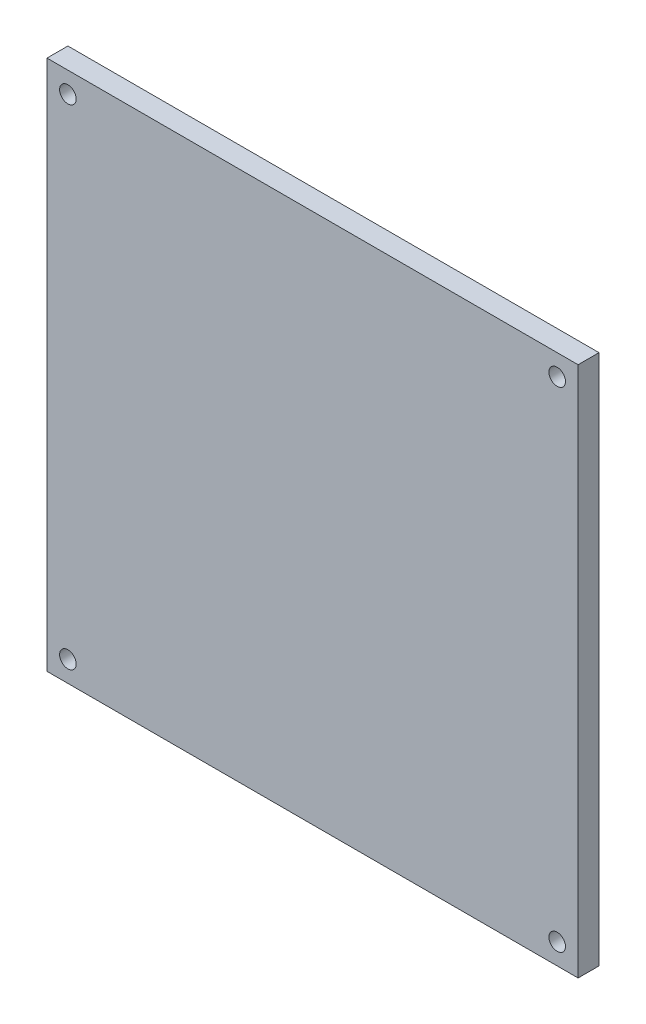
SolidWorks part; units mm, degrees
material "Полибутадиен (PB)"
ref_plane "Спереди" through (0, 0, 0) normal (0, 0, 1) x (1, 0, 0)
ref_plane "Сверху" through (0, 0, 0) normal (0, 1, 0) x (1, 0, 0)
ref_plane "Справа" through (0, 0, 0) normal (1, 0, 0) x (0, 0, -1)
curve "Импортированная кривая1"
curve "Импортированная кривая2"
curve "Импортированная кривая3"
curve "Импортированная кривая4"
curve "Импортированная кривая5"
curve "Импортированная кривая6"
curve "Импортированная кривая7"
curve "Импортированная кривая8"
curve "Импортированная кривая9"
curve "Импортированная кривая10"
curve "Импортированная кривая11"
curve "Импортированная кривая12"
curve "Импортированная кривая13"
curve "Импортированная кривая14"
curve "Импортированная кривая15"
curve "Импортированная кривая16"
curve "Импортированная кривая17"
curve "Импортированная кривая18"
curve "Импортированная кривая19"
curve "Импортированная кривая20"
curve "Импортированная кривая21"
curve "Импортированная кривая22"
curve "Импортированная кривая23"
curve "Импортированная кривая24"
curve "Импортированная кривая25"
curve "Импортированная кривая26"
curve "Импортированная кривая27"
curve "Импортированная кривая28"
curve "Импортированная кривая29"
curve "Импортированная кривая30"
curve "Импортированная кривая31"
curve "Импортированная кривая32"
curve "Импортированная кривая33"
curve "Импортированная кривая34"
curve "Импортированная кривая35"
curve "Импортированная кривая36"
curve "Импортированная кривая37"
curve "Импортированная кривая38"
curve "Импортированная кривая39"
curve "Импортированная кривая40"
curve "Импортированная кривая41"
curve "Импортированная кривая42"
curve "Импортированная кривая43"
curve "Импортированная кривая44"
curve "Импортированная кривая45"
curve "Импортированная кривая46"
curve "Импортированная кривая47"
curve "Импортированная кривая48"
curve "Импортированная кривая49"
curve "Импортированная кривая50"
curve "Импортированная кривая51"
curve "Импортированная кривая52"
curve "Импортированная кривая53"
curve "Импортированная кривая54"
curve "Импортированная кривая55"
curve "Импортированная кривая56"
curve "Импортированная кривая57"
curve "Импортированная кривая58"
curve "Импортированная кривая59"
curve "Импортированная кривая60"
curve "Импортированная кривая61"
curve "Импортированная кривая62"
curve "Импортированная кривая63"
curve "Импортированная кривая64"
curve "Импортированная кривая65"
curve "Импортированная кривая66"
curve "Импортированная кривая67"
curve "Импортированная кривая68"
curve "Импортированная кривая69"
curve "Импортированная кривая70"
curve "Импортированная кривая71"
curve "Импортированная кривая72"
curve "Импортированная кривая73"
curve "Импортированная кривая74"
curve "Импортированная кривая75"
curve "Импортированная кривая76"
curve "Импортированная кривая77"
curve "Импортированная кривая78"
curve "Импортированная кривая79"
curve "Импортированная кривая80"
curve "Импортированная кривая81"
curve "Импортированная кривая82"
curve "Импортированная кривая83"
curve "Импортированная кривая84"
curve "Импортированная кривая85"
curve "Импортированная кривая86"
curve "Импортированная кривая87"
curve "Импортированная кривая88"
curve "Импортированная кривая89"
curve "Импортированная кривая90"
curve "Импортированная кривая91"
curve "Импортированная кривая92"
curve "Импортированная кривая93"
curve "Импортированная кривая94"
curve "Импортированная кривая95"
curve "Импортированная кривая96"
curve "Импортированная кривая97"
curve "Импортированная кривая98"
curve "Импортированная кривая99"
curve "Импортированная кривая100"
curve "Импортированная кривая101"
curve "Импортированная кривая102"
curve "Импортированная кривая103"
curve "Импортированная кривая104"
curve "Импортированная кривая105"
curve "Импортированная кривая106"
curve "Импортированная кривая107"
curve "Импортированная кривая108"
curve "Импортированная кривая109"
curve "Импортированная кривая110"
curve "Импортированная кривая111"
curve "Импортированная кривая112"
curve "Импортированная кривая113"
curve "Импортированная кривая114"
curve "Импортированная кривая115"
curve "Импортированная кривая116"
curve "Импортированная кривая117"
curve "Импортированная кривая118"
curve "Импортированная кривая119"
curve "Импортированная кривая120"
curve "Импортированная кривая121"
curve "Импортированная кривая122"
curve "Импортированная кривая123"
curve "Импортированная кривая124"
curve "Импортированная кривая125"
curve "Импортированная кривая126"
curve "Импортированная кривая127"
curve "Импортированная кривая128"
curve "Импортированная кривая129"
curve "Импортированная кривая130"
curve "Импортированная кривая131"
curve "Импортированная кривая132"
curve "Импортированная кривая133"
curve "Импортированная кривая134"
curve "Импортированная кривая135"
curve "Импортированная кривая136"
curve "Импортированная кривая137"
curve "Импортированная кривая138"
curve "Импортированная кривая139"
curve "Импортированная кривая140"
curve "Импортированная кривая141"
curve "Импортированная кривая142"
curve "Импортированная кривая143"
curve "Импортированная кривая144"
curve "Импортированная кривая145"
curve "Импортированная кривая146"
curve "Импортированная кривая147"
curve "Импортированная кривая148"
curve "Импортированная кривая149"
curve "Импортированная кривая150"
curve "Импортированная кривая151"
curve "Импортированная кривая152"
curve "Импортированная кривая153"
curve "Импортированная кривая154"
curve "Импортированная кривая155"
curve "Импортированная кривая156"
curve "Импортированная кривая157"
curve "Импортированная кривая158"
curve "Импортированная кривая159"
curve "Импортированная кривая160"
curve "Импортированная кривая161"
curve "Импортированная кривая162"
curve "Импортированная кривая163"
curve "Импортированная кривая164"
curve "Импортированная кривая165"
curve "Импортированная кривая166"
curve "Импортированная кривая167"
curve "Импортированная кривая168"
curve "Импортированная кривая169"
curve "Импортированная кривая170"
curve "Импортированная кривая171"
curve "Импортированная кривая172"
curve "Импортированная кривая173"
curve "Импортированная кривая174"
curve "Импортированная кривая175"
curve "Импортированная кривая176"
curve "Импортированная кривая177"
curve "Импортированная кривая178"
curve "Импортированная кривая179"
curve "Импортированная кривая180"
curve "Импортированная кривая181"
curve "Импортированная кривая182"
curve "Импортированная кривая183"
curve "Импортированная кривая184"
curve "Импортированная кривая185"
curve "Импортированная кривая186"
curve "Импортированная кривая187"
curve "Импортированная кривая188"
curve "Импортированная кривая189"
curve "Импортированная кривая190"
curve "Импортированная кривая191"
curve "Импортированная кривая192"
curve "Импортированная кривая193"
curve "Импортированная кривая194"
curve "Импортированная кривая195"
curve "Импортированная кривая196"
curve "Импортированная кривая197"
curve "Импортированная кривая198"
curve "Импортированная кривая199"
curve "Импортированная кривая200"
curve "Импортированная кривая201"
curve "Импортированная кривая202"
curve "Импортированная кривая203"
curve "Импортированная кривая204"
curve "Импортированная кривая205"
curve "Импортированная кривая206"
curve "Импортированная кривая207"
curve "Импортированная кривая208"
curve "Импортированная кривая209"
curve "Импортированная кривая210"
curve "Импортированная кривая211"
curve "Импортированная кривая212"
curve "Импортированная кривая213"
curve "Импортированная кривая214"
curve "Импортированная кривая215"
curve "Импортированная кривая216"
curve "Импортированная кривая217"
curve "Импортированная кривая218"
curve "Импортированная кривая219"
curve "Импортированная кривая220"
curve "Импортированная кривая221"
curve "Импортированная кривая222"
curve "Импортированная кривая223"
curve "Импортированная кривая224"
curve "Импортированная кривая225"
curve "Импортированная кривая226"
curve "Импортированная кривая227"
curve "Импортированная кривая228"
curve "Импортированная кривая229"
curve "Импортированная кривая230"
curve "Импортированная кривая231"
curve "Импортированная кривая232"
curve "Импортированная кривая233"
curve "Импортированная кривая234"
curve "Импортированная кривая235"
curve "Импортированная кривая236"
curve "Импортированная кривая237"
curve "Импортированная кривая238"
curve "Импортированная кривая239"
curve "Импортированная кривая240"
curve "Импортированная кривая241"
curve "Импортированная кривая242"
curve "Импортированная кривая243"
curve "Импортированная кривая244"
curve "Импортированная кривая245"
curve "Импортированная кривая246"
curve "Импортированная кривая247"
curve "Импортированная кривая248"
curve "Импортированная кривая249"
curve "Импортированная кривая250"
curve "Импортированная кривая251"
curve "Импортированная кривая252"
curve "Импортированная кривая253"
curve "Импортированная кривая254"
curve "Импортированная кривая255"
curve "Импортированная кривая256"
curve "Импортированная кривая257"
curve "Импортированная кривая258"
curve "Импортированная кривая259"
curve "Импортированная кривая260"
curve "Импортированная кривая261"
curve "Импортированная кривая262"
curve "Импортированная кривая263"
curve "Импортированная кривая264"
curve "Импортированная кривая265"
curve "Импортированная кривая266"
curve "Импортированная кривая267"
curve "Импортированная кривая268"
curve "Импортированная кривая269"
curve "Импортированная кривая270"
curve "Импортированная кривая271"
curve "Импортированная кривая272"
curve "Импортированная кривая273"
curve "Импортированная кривая274"
curve "Импортированная кривая275"
curve "Импортированная кривая276"
curve "Импортированная кривая277"
curve "Импортированная кривая278"
curve "Импортированная кривая279"
curve "Импортированная кривая280"
curve "Импортированная кривая281"
curve "Импортированная кривая282"
curve "Импортированная кривая283"
curve "Импортированная кривая284"
curve "Импортированная кривая285"
curve "Импортированная кривая286"
curve "Импортированная кривая287"
curve "Импортированная кривая288"
curve "Импортированная кривая289"
curve "Импортированная кривая290"
curve "Импортированная кривая291"
curve "Импортированная кривая292"
curve "Импортированная кривая293"
curve "Импортированная кривая294"
curve "Импортированная кривая295"
curve "Импортированная кривая296"
curve "Импортированная кривая297"
curve "Импортированная кривая298"
curve "Импортированная кривая299"
curve "Импортированная кривая300"
curve "Импортированная кривая301"
curve "Импортированная кривая302"
curve "Импортированная кривая303"
curve "Импортированная кривая304"
curve "Импортированная кривая305"
curve "Импортированная кривая306"
curve "Импортированная кривая307"
curve "Импортированная кривая308"
curve "Импортированная кривая309"
curve "Импортированная кривая310"
curve "Импортированная кривая311"
curve "Импортированная кривая312"
curve "Импортированная кривая313"
curve "Импортированная кривая314"
curve "Импортированная кривая315"
curve "Импортированная кривая316"
curve "Импортированная кривая317"
curve "Импортированная кривая318"
curve "Импортированная кривая319"
curve "Импортированная кривая320"
curve "Импортированная кривая321"
curve "Импортированная кривая322"
curve "Импортированная кривая323"
curve "Импортированная кривая324"
curve "Импортированная кривая325"
curve "Импортированная кривая326"
curve "Импортированная кривая327"
curve "Импортированная кривая328"
curve "Импортированная кривая329"
curve "Импортированная кривая330"
curve "Импортированная кривая331"
curve "Импортированная кривая332"
curve "Импортированная кривая333"
curve "Импортированная кривая334"
curve "Импортированная кривая335"
curve "Импортированная кривая336"
curve "Импортированная кривая337"
curve "Импортированная кривая338"
curve "Импортированная кривая339"
curve "Импортированная кривая340"
curve "Импортированная кривая341"
curve "Импортированная кривая342"
curve "Импортированная кривая343"
curve "Импортированная кривая344"
curve "Импортированная кривая345"
curve "Импортированная кривая346"
curve "Импортированная кривая347"
curve "Импортированная кривая348"
curve "Импортированная кривая349"
curve "Импортированная кривая350"
curve "Импортированная кривая351"
curve "Импортированная кривая352"
curve "Импортированная кривая353"
curve "Импортированная кривая354"
curve "Импортированная кривая355"
curve "Импортированная кривая356"
curve "Импортированная кривая357"
curve "Импортированная кривая358"
curve "Импортированная кривая359"
curve "Импортированная кривая360"
curve "Импортированная кривая361"
curve "Импортированная кривая362"
curve "Импортированная кривая363"
curve "Импортированная кривая364"
curve "Импортированная кривая365"
curve "Импортированная кривая366"
curve "Импортированная кривая367"
curve "Импортированная кривая368"
curve "Импортированная кривая369"
curve "Импортированная кривая370"
curve "Импортированная кривая371"
curve "Импортированная кривая372"
curve "Импортированная кривая373"
curve "Импортированная кривая374"
curve "Импортированная кривая375"
curve "Импортированная кривая376"
curve "Импортированная кривая377"
curve "Импортированная кривая378"
curve "Импортированная кривая379"
curve "Импортированная кривая380"
curve "Импортированная кривая381"
curve "Импортированная кривая382"
curve "Импортированная кривая383"
curve "Импортированная кривая384"
curve "Импортированная кривая385"
curve "Импортированная кривая386"
curve "Импортированная кривая387"
curve "Импортированная кривая388"
curve "Импортированная кривая389"
curve "Импортированная кривая390"
curve "Импортированная кривая391"
curve "Импортированная кривая392"
curve "Импортированная кривая393"
curve "Импортированная кривая394"
curve "Импортированная кривая395"
curve "Импортированная кривая396"
curve "Импортированная кривая397"
curve "Импортированная кривая398"
curve "Импортированная кривая399"
curve "Импортированная кривая400"
curve "Импортированная кривая401"
curve "Импортированная кривая402"
curve "Импортированная кривая403"
curve "Импортированная кривая404"
curve "Импортированная кривая405"
curve "Импортированная кривая406"
curve "Импортированная кривая407"
curve "Импортированная кривая408"
curve "Импортированная кривая409"
curve "Импортированная кривая410"
curve "Импортированная кривая411"
curve "Импортированная кривая412"
curve "Импортированная кривая413"
curve "Импортированная кривая414"
curve "Импортированная кривая415"
curve "Импортированная кривая416"
curve "Импортированная кривая417"
curve "Импортированная кривая418"
curve "Импортированная кривая419"
curve "Импортированная кривая420"
curve "Импортированная кривая421"
curve "Импортированная кривая422"
curve "Импортированная кривая423"
curve "Импортированная кривая424"
curve "Импортированная кривая425"
curve "Импортированная кривая426"
curve "Импортированная кривая427"
curve "Импортированная кривая428"
curve "Импортированная кривая429"
curve "Импортированная кривая430"
curve "Импортированная кривая431"
curve "Импортированная кривая432"
curve "Импортированная кривая433"
curve "Импортированная кривая434"
curve "Импортированная кривая435"
curve "Импортированная кривая436"
curve "Импортированная кривая437"
curve "Импортированная кривая438"
curve "Импортированная кривая439"
curve "Импортированная кривая440"
curve "Импортированная кривая441"
curve "Импортированная кривая442"
curve "Импортированная кривая443"
curve "Импортированная кривая444"
curve "Импортированная кривая445"
curve "Импортированная кривая446"
curve "Импортированная кривая447"
curve "Импортированная кривая448"
curve "Импортированная кривая449"
curve "Импортированная кривая450"
curve "Импортированная кривая451"
curve "Импортированная кривая452"
curve "Импортированная кривая453"
curve "Импортированная кривая454"
curve "Импортированная кривая455"
curve "Импортированная кривая456"
curve "Импортированная кривая457"
curve "Импортированная кривая458"
curve "Импортированная кривая459"
curve "Импортированная кривая460"
curve "Импортированная кривая461"
curve "Импортированная кривая462"
curve "Импортированная кривая463"
curve "Импортированная кривая464"
curve "Импортированная кривая465"
curve "Импортированная кривая466"
curve "Импортированная кривая467"
curve "Импортированная кривая468"
curve "Импортированная кривая469"
curve "Импортированная кривая470"
curve "Импортированная кривая471"
curve "Импортированная кривая472"
curve "Импортированная кривая473"
curve "Импортированная кривая474"
curve "Импортированная кривая475"
curve "Импортированная кривая476"
curve "Импортированная кривая477"
curve "Импортированная кривая478"
curve "Импортированная кривая479"
curve "Импортированная кривая480"
curve "Импортированная кривая481"
curve "Импортированная кривая482"
curve "Импортированная кривая483"
curve "Импортированная кривая484"
curve "Импортированная кривая485"
curve "Импортированная кривая486"
curve "Импортированная кривая487"
curve "Импортированная кривая488"
curve "Импортированная кривая489"
curve "Импортированная кривая490"
curve "Импортированная кривая491"
curve "Импортированная кривая492"
curve "Импортированная кривая493"
curve "Импортированная кривая494"
curve "Импортированная кривая495"
curve "Импортированная кривая496"
curve "Импортированная кривая497"
curve "Импортированная кривая498"
curve "Импортированная кривая499"
curve "Импортированная кривая500"
curve "Импортированная кривая501"
curve "Импортированная кривая502"
curve "Импортированная кривая503"
curve "Импортированная кривая504"
curve "Импортированная кривая505"
curve "Импортированная кривая506"
curve "Импортированная кривая507"
curve "Импортированная кривая508"
curve "Импортированная кривая509"
curve "Импортированная кривая510"
curve "Импортированная кривая511"
curve "Импортированная кривая512"
curve "Импортированная кривая513"
curve "Импортированная кривая514"
curve "Импортированная кривая515"
curve "Импортированная кривая516"
curve "Импортированная кривая517"
curve "Импортированная кривая518"
curve "Импортированная кривая519"
curve "Импортированная кривая520"
curve "Импортированная кривая521"
curve "Импортированная кривая522"
curve "Импортированная кривая523"
curve "Импортированная кривая524"
curve "Импортированная кривая525"
curve "Импортированная кривая526"
curve "Импортированная кривая527"
curve "Импортированная кривая528"
curve "Импортированная кривая529"
curve "Импортированная кривая530"
curve "Импортированная кривая531"
curve "Импортированная кривая532"
curve "Импортированная кривая533"
curve "Импортированная кривая534"
curve "Импортированная кривая535"
curve "Импортированная кривая536"
curve "Импортированная кривая537"
curve "Импортированная кривая538"
curve "Импортированная кривая539"
curve "Импортированная кривая540"
curve "Импортированная кривая541"
curve "Импортированная кривая542"
curve "Импортированная кривая543"
curve "Импортированная кривая544"
curve "Импортированная кривая545"
curve "Импортированная кривая546"
curve "Импортированная кривая547"
curve "Импортированная кривая548"
curve "Импортированная кривая549"
curve "Импортированная кривая550"
curve "Импортированная кривая551"
curve "Импортированная кривая552"
curve "Импортированная кривая553"
curve "Импортированная кривая554"
curve "Импортированная кривая555"
curve "Импортированная кривая556"
curve "Импортированная кривая557"
curve "Импортированная кривая558"
curve "Импортированная кривая559"
curve "Импортированная кривая560"
curve "Импортированная кривая561"
curve "Импортированная кривая562"
curve "Импортированная кривая563"
curve "Импортированная кривая564"
curve "Импортированная кривая565"
curve "Импортированная кривая566"
curve "Импортированная кривая567"
curve "Импортированная кривая568"
curve "Импортированная кривая569"
curve "Импортированная кривая570"
curve "Импортированная кривая571"
curve "Импортированная кривая572"
curve "Импортированная кривая573"
curve "Импортированная кривая574"
curve "Импортированная кривая575"
curve "Импортированная кривая576"
curve "Импортированная кривая577"
curve "Импортированная кривая578"
curve "Импортированная кривая579"
curve "Импортированная кривая580"
curve "Импортированная кривая581"
curve "Импортированная кривая582"
curve "Импортированная кривая583"
curve "Импортированная кривая584"
curve "Импортированная кривая585"
curve "Импортированная кривая586"
curve "Импортированная кривая587"
curve "Импортированная кривая588"
curve "Импортированная кривая589"
curve "Импортированная кривая590"
curve "Импортированная кривая591"
curve "Импортированная кривая592"
curve "Импортированная кривая593"
curve "Импортированная кривая594"
curve "Импортированная кривая595"
curve "Импортированная кривая596"
curve "Импортированная кривая597"
curve "Импортированная кривая598"
curve "Импортированная кривая599"
curve "Импортированная кривая600"
curve "Импортированная кривая601"
curve "Импортированная кривая602"
curve "Импортированная кривая603"
curve "Импортированная кривая604"
curve "Импортированная кривая605"
curve "Импортированная кривая606"
curve "Импортированная кривая607"
curve "Импортированная кривая608"
curve "Импортированная кривая609"
curve "Импортированная кривая610"
curve "Импортированная кривая611"
curve "Импортированная кривая612"
curve "Импортированная кривая613"
curve "Импортированная кривая614"
curve "Импортированная кривая615"
curve "Импортированная кривая616"
curve "Импортированная кривая617"
curve "Импортированная кривая618"
curve "Импортированная кривая619"
curve "Импортированная кривая620"
curve "Импортированная кривая621"
curve "Импортированная кривая622"
curve "Импортированная кривая623"
curve "Импортированная кривая624"
curve "Импортированная кривая625"
curve "Импортированная кривая626"
curve "Импортированная кривая627"
curve "Импортированная кривая628"
curve "Импортированная кривая629"
curve "Импортированная кривая630"
curve "Импортированная кривая631"
curve "Импортированная кривая632"
curve "Импортированная кривая633"
curve "Импортированная кривая634"
curve "Импортированная кривая635"
curve "Импортированная кривая636"
curve "Импортированная кривая637"
curve "Импортированная кривая638"
curve "Импортированная кривая639"
curve "Импортированная кривая640"
curve "Импортированная кривая641"
curve "Импортированная кривая642"
curve "Импортированная кривая643"
curve "Импортированная кривая644"
curve "Импортированная кривая645"
curve "Импортированная кривая646"
curve "Импортированная кривая647"
curve "Импортированная кривая648"
curve "Импортированная кривая649"
curve "Импортированная кривая650"
curve "Импортированная кривая651"
curve "Импортированная кривая652"
curve "Импортированная кривая653"
curve "Импортированная кривая654"
curve "Импортированная кривая655"
curve "Импортированная кривая656"
curve "Импортированная кривая657"
curve "Импортированная кривая658"
curve "Импортированная кривая659"
curve "Импортированная кривая660"
curve "Импортированная кривая661"
curve "Импортированная кривая662"
curve "Импортированная кривая663"
curve "Импортированная кривая664"
curve "Импортированная кривая665"
curve "Импортированная кривая666"
curve "Импортированная кривая667"
curve "Импортированная кривая668"
curve "Импортированная кривая669"
curve "Импортированная кривая670"
curve "Импортированная кривая671"
curve "Импортированная кривая672"
curve "Импортированная кривая673"
curve "Импортированная кривая674"
curve "Импортированная кривая675"
curve "Импортированная кривая676"
curve "Импортированная кривая677"
curve "Импортированная кривая678"
curve "Импортированная кривая679"
curve "Импортированная кривая680"
curve "Импортированная кривая681"
curve "Импортированная кривая682"
curve "Импортированная кривая683"
curve "Импортированная кривая684"
curve "Импортированная кривая685"
curve "Импортированная кривая686"
curve "Импортированная кривая687"
curve "Импортированная кривая688"
curve "Импортированная кривая689"
curve "Импортированная кривая690"
curve "Импортированная кривая691"
curve "Импортированная кривая692"
curve "Импортированная кривая693"
curve "Импортированная кривая694"
curve "Импортированная кривая695"
curve "Импортированная кривая696"
curve "Импортированная кривая697"
curve "Импортированная кривая698"
curve "Импортированная кривая699"
curve "Импортированная кривая700"
curve "Импортированная кривая701"
curve "Импортированная кривая702"
curve "Импортированная кривая703"
curve "Импортированная кривая704"
curve "Импортированная кривая705"
curve "Импортированная кривая706"
curve "Импортированная кривая707"
curve "Импортированная кривая708"
curve "Импортированная кривая709"
curve "Импортированная кривая710"
curve "Импортированная кривая711"
curve "Импортированная кривая712"
curve "Импортированная кривая713"
curve "Импортированная кривая714"
curve "Импортированная кривая715"
curve "Импортированная кривая716"
curve "Импортированная кривая717"
curve "Импортированная кривая718"
curve "Импортированная кривая719"
curve "Импортированная кривая720"
curve "Импортированная кривая721"
curve "Импортированная кривая722"
curve "Импортированная кривая723"
curve "Импортированная кривая724"
curve "Импортированная кривая725"
curve "Импортированная кривая726"
curve "Импортированная кривая727"
curve "Импортированная кривая728"
curve "Импортированная кривая729"
curve "Импортированная кривая730"
curve "Импортированная кривая731"
curve "Импортированная кривая732"
curve "Импортированная кривая733"
curve "Импортированная кривая734"
curve "Импортированная кривая735"
curve "Импортированная кривая736"
curve "Импортированная кривая737"
curve "Импортированная кривая738"
curve "Импортированная кривая739"
curve "Импортированная кривая740"
curve "Импортированная кривая741"
curve "Импортированная кривая742"
curve "Импортированная кривая743"
curve "Импортированная кривая744"
curve "Импортированная кривая745"
curve "Импортированная кривая746"
curve "Импортированная кривая747"
curve "Импортированная кривая748"
curve "Импортированная кривая749"
curve "Импортированная кривая750"
curve "Импортированная кривая751"
curve "Импортированная кривая752"
curve "Импортированная кривая753"
curve "Импортированная кривая754"
curve "Импортированная кривая755"
curve "Импортированная кривая756"
curve "Импортированная кривая757"
curve "Импортированная кривая758"
curve "Импортированная кривая759"
curve "Импортированная кривая760"
curve "Импортированная кривая761"
curve "Импортированная кривая762"
curve "Импортированная кривая763"
curve "Импортированная кривая764"
curve "Импортированная кривая765"
curve "Импортированная кривая766"
curve "Импортированная кривая767"
curve "Импортированная кривая768"
curve "Импортированная кривая769"
curve "Импортированная кривая770"
curve "Импортированная кривая771"
curve "Импортированная кривая772"
curve "Импортированная кривая773"
curve "Импортированная кривая774"
curve "Импортированная кривая775"
curve "Импортированная кривая776"
curve "Импортированная кривая777"
curve "Импортированная кривая778"
curve "Импортированная кривая779"
curve "Импортированная кривая780"
curve "Импортированная кривая781"
curve "Импортированная кривая782"
curve "Импортированная кривая783"
curve "Импортированная кривая784"
curve "Импортированная кривая785"
curve "Импортированная кривая786"
curve "Импортированная кривая787"
curve "Импортированная кривая788"
curve "Импортированная кривая789"
curve "Импортированная кривая790"
curve "Импортированная кривая791"
curve "Импортированная кривая792"
curve "Импортированная кривая793"
curve "Импортированная кривая794"
curve "Импортированная кривая795"
curve "Импортированная кривая796"
curve "Импортированная кривая797"
curve "Импортированная кривая798"
curve "Импортированная кривая799"
curve "Импортированная кривая800"
curve "Импортированная кривая801"
curve "Импортированная кривая802"
curve "Импортированная кривая803"
curve "Импортированная кривая804"
curve "Импортированная кривая805"
curve "Импортированная кривая806"
curve "Импортированная кривая807"
curve "Импортированная кривая808"
curve "Импортированная кривая809"
curve "Импортированная кривая810"
curve "Импортированная кривая811"
curve "Импортированная кривая812"
curve "Импортированная кривая813"
curve "Импортированная кривая814"
curve "Импортированная кривая815"
curve "Импортированная кривая816"
curve "Импортированная кривая817"
curve "Импортированная кривая818"
curve "Импортированная кривая819"
curve "Импортированная кривая820"
curve "Импортированная кривая821"
curve "Импортированная кривая822"
curve "Импортированная кривая823"
curve "Импортированная кривая824"
curve "Импортированная кривая825"
curve "Импортированная кривая826"
curve "Импортированная кривая827"
curve "Импортированная кривая828"
curve "Импортированная кривая829"
curve "Импортированная кривая830"
curve "Импортированная кривая831"
curve "Импортированная кривая832"
curve "Импортированная кривая833"
curve "Импортированная кривая834"
curve "Импортированная кривая835"
curve "Импортированная кривая836"
curve "Импортированная кривая837"
curve "Импортированная кривая838"
curve "Импортированная кривая839"
curve "Импортированная кривая840"
curve "Импортированная кривая841"
curve "Импортированная кривая842"
curve "Импортированная кривая843"
curve "Импортированная кривая844"
curve "Импортированная кривая845"
curve "Импортированная кривая846"
curve "Импортированная кривая847"
curve "Импортированная кривая848"
curve "Импортированная кривая849"
curve "Импортированная кривая850"
curve "Импортированная кривая851"
curve "Импортированная кривая852"
curve "Импортированная кривая853"
curve "Импортированная кривая854"
curve "Импортированная кривая855"
curve "Импортированная кривая856"
curve "Импортированная кривая857"
curve "Импортированная кривая858"
curve "Импортированная кривая859"
curve "Импортированная кривая860"
curve "Импортированная кривая861"
curve "Импортированная кривая862"
curve "Импортированная кривая863"
curve "Импортированная кривая864"
curve "Импортированная кривая865"
curve "Импортированная кривая866"
curve "Импортированная кривая867"
curve "Импортированная кривая868"
curve "Импортированная кривая869"
curve "Импортированная кривая870"
curve "Импортированная кривая871"
curve "Импортированная кривая872"
curve "Импортированная кривая873"
curve "Импортированная кривая874"
curve "Импортированная кривая875"
curve "Импортированная кривая876"
curve "Импортированная кривая877"
curve "Импортированная кривая878"
curve "Импортированная кривая879"
curve "Импортированная кривая880"
curve "Импортированная кривая881"
curve "Импортированная кривая882"
curve "Импортированная кривая883"
curve "Импортированная кривая884"
curve "Импортированная кривая885"
curve "Импортированная кривая886"
curve "Импортированная кривая887"
curve "Импортированная кривая888"
curve "Импортированная кривая889"
curve "Импортированная кривая890"
curve "Импортированная кривая891"
curve "Импортированная кривая892"
curve "Импортированная кривая893"
curve "Импортированная кривая894"
curve "Импортированная кривая895"
curve "Импортированная кривая896"
curve "Импортированная кривая897"
curve "Импортированная кривая898"
curve "Импортированная кривая899"
curve "Импортированная кривая900"
curve "Импортированная кривая901"
curve "Импортированная кривая902"
curve "Импортированная кривая903"
curve "Импортированная кривая904"
curve "Импортированная кривая905"
curve "Импортированная кривая906"
curve "Импортированная кривая907"
curve "Импортированная кривая908"
curve "Импортированная кривая909"
curve "Импортированная кривая910"
curve "Импортированная кривая911"
curve "Импортированная кривая912"
curve "Импортированная кривая913"
curve "Импортированная кривая914"
curve "Импортированная кривая915"
curve "Импортированная кривая916"
curve "Импортированная кривая917"
curve "Импортированная кривая918"
curve "Импортированная кривая919"
curve "Импортированная кривая920"
curve "Импортированная кривая921"
curve "Импортированная кривая922"
curve "Импортированная кривая923"
curve "Импортированная кривая924"
curve "Импортированная кривая925"
curve "Импортированная кривая926"
curve "Импортированная кривая927"
curve "Импортированная кривая928"
curve "Импортированная кривая929"
curve "Импортированная кривая930"
curve "Импортированная кривая931"
curve "Импортированная кривая932"
curve "Импортированная кривая933"
curve "Импортированная кривая934"
curve "Импортированная кривая935"
curve "Импортированная кривая936"
curve "Импортированная кривая937"
curve "Импортированная кривая938"
curve "Импортированная кривая939"
curve "Импортированная кривая940"
curve "Импортированная кривая941"
curve "Импортированная кривая942"
curve "Импортированная кривая943"
curve "Импортированная кривая944"
curve "Импортированная кривая945"
curve "Импортированная кривая946"
curve "Импортированная кривая947"
curve "Импортированная кривая948"
curve "Импортированная кривая949"
curve "Импортированная кривая950"
curve "Импортированная кривая951"
curve "Импортированная кривая952"
curve "Импортированная кривая953"
curve "Импортированная кривая954"
curve "Импортированная кривая955"
curve "Импортированная кривая956"
curve "Импортированная кривая957"
curve "Импортированная кривая958"
curve "Импортированная кривая959"
curve "Импортированная кривая960"
curve "Импортированная кривая961"
curve "Импортированная кривая962"
curve "Импортированная кривая963"
curve "Импортированная кривая964"
curve "Импортированная кривая965"
curve "Импортированная кривая966"
curve "Импортированная кривая967"
curve "Импортированная кривая968"
curve "Импортированная кривая969"
curve "Импортированная кривая970"
curve "Импортированная кривая971"
curve "Импортированная кривая972"
curve "Импортированная кривая973"
curve "Импортированная кривая974"
curve "Импортированная кривая975"
curve "Импортированная кривая976"
curve "Импортированная кривая977"
curve "Импортированная кривая978"
curve "Импортированная кривая979"
curve "Импортированная кривая980"
curve "Импортированная кривая981"
curve "Импортированная кривая982"
curve "Импортированная кривая983"
curve "Импортированная кривая984"
curve "Импортированная кривая985"
curve "Импортированная кривая986"
curve "Импортированная кривая987"
curve "Импортированная кривая988"
curve "Импортированная кривая989"
curve "Импортированная кривая990"
curve "Импортированная кривая991"
curve "Импортированная кривая992"
curve "Импортированная кривая993"
curve "Импортированная кривая994"
curve "Импортированная кривая995"
curve "Импортированная кривая996"
curve "Импортированная кривая997"
curve "Импортированная кривая998"
curve "Импортированная кривая999"
curve "Импортированная кривая1000"
curve "Импортированная кривая1001"
curve "Импортированная кривая1002"
curve "Импортированная кривая1003"
curve "Импортированная кривая1004"
curve "Импортированная кривая1005"
curve "Импортированная кривая1006"
curve "Импортированная кривая1007"
curve "Импортированная кривая1008"
curve "Импортированная кривая1009"
curve "Импортированная кривая1010"
curve "Импортированная кривая1011"
curve "Импортированная кривая1012"
curve "Импортированная кривая1013"
curve "Импортированная кривая1014"
curve "Импортированная кривая1015"
curve "Импортированная кривая1016"
curve "Импортированная кривая1017"
curve "Импортированная кривая1018"
curve "Импортированная кривая1019"
curve "Импортированная кривая1020"
curve "Импортированная кривая1021"
curve "Импортированная кривая1022"
curve "Импортированная кривая1023"
curve "Импортированная кривая1024"
curve "Импортированная кривая1025"
curve "Импортированная кривая1026"
curve "Импортированная кривая1027"
curve "Импортированная кривая1028"
curve "Импортированная кривая1029"
curve "Импортированная кривая1030"
curve "Импортированная кривая1031"
curve "Импортированная кривая1032"
curve "Импортированная кривая1033"
curve "Импортированная кривая1034"
curve "Импортированная кривая1035"
curve "Импортированная кривая1036"
curve "Импортированная кривая1037"
curve "Импортированная кривая1038"
curve "Импортированная кривая1039"
curve "Импортированная кривая1040"
curve "Импортированная кривая1041"
curve "Импортированная кривая1042"
curve "Импортированная кривая1043"
curve "Импортированная кривая1044"
curve "Импортированная кривая1045"
curve "Импортированная кривая1046"
curve "Импортированная кривая1047"
curve "Импортированная кривая1048"
curve "Импортированная кривая1049"
curve "Импортированная кривая1050"
curve "Импортированная кривая1051"
curve "Импортированная кривая1052"
curve "Импортированная кривая1053"
curve "Импортированная кривая1054"
curve "Импортированная кривая1055"
curve "Импортированная кривая1056"
curve "Импортированная кривая1057"
curve "Импортированная кривая1058"
curve "Импортированная кривая1059"
curve "Импортированная кривая1060"
curve "Импортированная кривая1061"
curve "Импортированная кривая1062"
curve "Импортированная кривая1063"
curve "Импортированная кривая1064"
curve "Импортированная кривая1065"
curve "Импортированная кривая1066"
curve "Импортированная кривая1067"
curve "Импортированная кривая1068"
curve "Импортированная кривая1069"
curve "Импортированная кривая1070"
curve "Импортированная кривая1071"
curve "Импортированная кривая1072"
curve "Импортированная кривая1073"
curve "Импортированная кривая1074"
curve "Импортированная кривая1075"
curve "Импортированная кривая1076"
curve "Импортированная кривая1077"
curve "Импортированная кривая1078"
curve "Импортированная кривая1079"
curve "Импортированная кривая1080"
curve "Импортированная кривая1081"
curve "Импортированная кривая1082"
curve "Импортированная кривая1083"
curve "Импортированная кривая1084"
curve "Импортированная кривая1085"
curve "Импортированная кривая1086"
curve "Импортированная кривая1087"
curve "Импортированная кривая1088"
curve "Импортированная кривая1089"
curve "Импортированная кривая1090"
curve "Импортированная кривая1091"
curve "Импортированная кривая1092"
curve "Импортированная кривая1093"
curve "Импортированная кривая1094"
curve "Импортированная кривая1095"
curve "Импортированная кривая1096"
curve "Импортированная кривая1097"
curve "Импортированная кривая1098"
curve "Импортированная кривая1099"
curve "Импортированная кривая1100"
curve "Импортированная кривая1101"
curve "Импортированная кривая1102"
curve "Импортированная кривая1103"
curve "Импортированная кривая1104"
curve "Импортированная кривая1105"
curve "Импортированная кривая1106"
curve "Импортированная кривая1107"
curve "Импортированная кривая1108"
curve "Импортированная кривая1109"
curve "Импортированная кривая1110"
curve "Импортированная кривая1111"
curve "Импортированная кривая1112"
curve "Импортированная кривая1113"
curve "Импортированная кривая1114"
curve "Импортированная кривая1115"
curve "Импортированная кривая1116"
curve "Импортированная кривая1117"
curve "Импортированная кривая1118"
curve "Импортированная кривая1119"
curve "Импортированная кривая1120"
curve "Импортированная кривая1121"
curve "Импортированная кривая1122"
curve "Импортированная кривая1123"
curve "Импортированная кривая1124"
curve "Импортированная кривая1125"
curve "Импортированная кривая1126"
curve "Импортированная кривая1127"
curve "Импортированная кривая1128"
curve "Импортированная кривая1129"
curve "Импортированная кривая1130"
curve "Импортированная кривая1131"
curve "Импортированная кривая1132"
curve "Импортированная кривая1133"
curve "Импортированная кривая1134"
curve "Импортированная кривая1135"
curve "Импортированная кривая1136"
curve "Импортированная кривая1137"
curve "Импортированная кривая1138"
curve "Импортированная кривая1139"
curve "Импортированная кривая1140"
curve "Импортированная кривая1141"
curve "Импортированная кривая1142"
curve "Импортированная кривая1143"
curve "Импортированная кривая1144"
curve "Импортированная кривая1145"
curve "Импортированная кривая1146"
curve "Импортированная кривая1147"
curve "Импортированная кривая1148"
curve "Импортированная кривая1149"
curve "Импортированная кривая1150"
curve "Импортированная кривая1151"
curve "Импортированная кривая1152"
curve "Импортированная кривая1153"
curve "Импортированная кривая1154"
curve "Импортированная кривая1155"
curve "Импортированная кривая1156"
curve "Импортированная кривая1157"
curve "Импортированная кривая1158"
curve "Импортированная кривая1159"
curve "Импортированная кривая1160"
curve "Импортированная кривая1161"
curve "Импортированная кривая1162"
curve "Импортированная кривая1163"
curve "Импортированная кривая1164"
curve "Импортированная кривая1165"
curve "Импортированная кривая1166"
curve "Импортированная кривая1167"
curve "Импортированная кривая1168"
curve "Импортированная кривая1169"
curve "Импортированная кривая1170"
curve "Импортированная кривая1171"
curve "Импортированная кривая1172"
curve "Импортированная кривая1173"
curve "Импортированная кривая1174"
curve "Импортированная кривая1175"
curve "Импортированная кривая1176"
curve "Импортированная кривая1177"
curve "Импортированная кривая1178"
curve "Импортированная кривая1179"
curve "Импортированная кривая1180"
curve "Импортированная кривая1181"
curve "Импортированная кривая1182"
curve "Импортированная кривая1183"
curve "Импортированная кривая1184"
curve "Импортированная кривая1185"
curve "Импортированная кривая1186"
curve "Импортированная кривая1187"
curve "Импортированная кривая1188"
curve "Импортированная кривая1189"
curve "Импортированная кривая1190"
curve "Импортированная кривая1191"
curve "Импортированная кривая1192"
curve "Импортированная кривая1193"
curve "Импортированная кривая1194"
curve "Импортированная кривая1195"
curve "Импортированная кривая1196"
curve "Импортированная кривая1197"
curve "Импортированная кривая1198"
curve "Импортированная кривая1199"
curve "Импортированная кривая1200"
curve "Импортированная кривая1201"
curve "Импортированная кривая1202"
curve "Импортированная кривая1203"
curve "Импортированная кривая1204"
curve "Импортированная кривая1205"
curve "Импортированная кривая1206"
curve "Импортированная кривая1207"
curve "Импортированная кривая1208"
curve "Импортированная кривая1209"
curve "Импортированная кривая1210"
curve "Импортированная кривая1211"
curve "Импортированная кривая1212"
curve "Импортированная кривая1213"
curve "Импортированная кривая1214"
curve "Импортированная кривая1215"
curve "Импортированная кривая1216"
curve "Импортированная кривая1217"
curve "Импортированная кривая1218"
curve "Импортированная кривая1219"
curve "Импортированная кривая1220"
curve "Импортированная кривая1221"
curve "Импортированная кривая1222"
curve "Импортированная кривая1223"
curve "Импортированная кривая1224"
curve "Импортированная кривая1225"
curve "Импортированная кривая1226"
curve "Импортированная кривая1227"
curve "Импортированная кривая1228"
curve "Импортированная кривая1229"
curve "Импортированная кривая1230"
curve "Импортированная кривая1231"
curve "Импортированная кривая1232"
curve "Импортированная кривая1233"
curve "Импортированная кривая1234"
curve "Импортированная кривая1235"
curve "Импортированная кривая1236"
curve "Импортированная кривая1237"
curve "Импортированная кривая1238"
curve "Импортированная кривая1239"
curve "Импортированная кривая1240"
curve "Импортированная кривая1241"
curve "Импортированная кривая1242"
curve "Импортированная кривая1243"
curve "Импортированная кривая1244"
curve "Импортированная кривая1245"
curve "Импортированная кривая1246"
curve "Импортированная кривая1247"
curve "Импортированная кривая1248"
curve "Импортированная кривая1249"
curve "Импортированная кривая1250"
curve "Импортированная кривая1251"
curve "Импортированная кривая1252"
curve "Импортированная кривая1253"
curve "Импортированная кривая1254"
curve "Импортированная кривая1255"
curve "Импортированная кривая1256"
curve "Импортированная кривая1257"
curve "Импортированная кривая1258"
curve "Импортированная кривая1259"
curve "Импортированная кривая1260"
curve "Импортированная кривая1261"
curve "Импортированная кривая1262"
curve "Импортированная кривая1263"
curve "Импортированная кривая1264"
curve "Импортированная кривая1265"
curve "Импортированная кривая1266"
curve "Импортированная кривая1267"
curve "Импортированная кривая1268"
curve "Импортированная кривая1269"
curve "Импортированная кривая1270"
curve "Импортированная кривая1271"
curve "Импортированная кривая1272"
curve "Импортированная кривая1273"
curve "Импортированная кривая1274"
curve "Импортированная кривая1275"
curve "Импортированная кривая1276"
curve "Импортированная кривая1277"
curve "Импортированная кривая1278"
curve "Импортированная кривая1279"
curve "Импортированная кривая1280"
curve "Импортированная кривая1281"
curve "Импортированная кривая1282"
curve "Импортированная кривая1283"
curve "Импортированная кривая1284"
curve "Импортированная кривая1285"
curve "Импортированная кривая1286"
curve "Импортированная кривая1287"
curve "Импортированная кривая1288"
curve "Импортированная кривая1289"
curve "Импортированная кривая1290"
curve "Импортированная кривая1291"
curve "Импортированная кривая1292"
curve "Импортированная кривая1293"
curve "Импортированная кривая1294"
curve "Импортированная кривая1295"
curve "Импортированная кривая1296"
curve "Импортированная кривая1297"
curve "Импортированная кривая1298"
curve "Импортированная кривая1299"
curve "Импортированная кривая1300"
curve "Импортированная кривая1301"
curve "Импортированная кривая1302"
curve "Импортированная кривая1303"
curve "Импортированная кривая1304"
curve "Импортированная кривая1305"
curve "Импортированная кривая1306"
curve "Импортированная кривая1307"
curve "Импортированная кривая1308"
curve "Импортированная кривая1309"
curve "Импортированная кривая1310"
curve "Импортированная кривая1311"
curve "Импортированная кривая1312"
curve "Импортированная кривая1313"
curve "Импортированная кривая1314"
curve "Импортированная кривая1315"
curve "Импортированная кривая1316"
curve "Импортированная кривая1317"
curve "Импортированная кривая1318"
curve "Импортированная кривая1319"
curve "Импортированная кривая1320"
curve "Импортированная кривая1321"
curve "Импортированная кривая1322"
curve "Импортированная кривая1323"
curve "Импортированная кривая1324"
curve "Импортированная кривая1325"
curve "Импортированная кривая1326"
curve "Импортированная кривая1327"
curve "Импортированная кривая1328"
curve "Импортированная кривая1329"
curve "Импортированная кривая1330"
curve "Импортированная кривая1331"
curve "Импортированная кривая1332"
curve "Импортированная кривая1333"
curve "Импортированная кривая1334"
curve "Импортированная кривая1335"
curve "Импортированная кривая1336"
curve "Импортированная кривая1337"
curve "Импортированная кривая1338"
curve "Импортированная кривая1339"
curve "Импортированная кривая1340"
curve "Импортированная кривая1341"
curve "Импортированная кривая1342"
curve "Импортированная кривая1343"
curve "Импортированная кривая1344"
curve "Импортированная кривая1345"
curve "Импортированная кривая1346"
curve "Импортированная кривая1347"
curve "Импортированная кривая1348"
curve "Импортированная кривая1349"
curve "Импортированная кривая1350"
curve "Импортированная кривая1351"
curve "Импортированная кривая1352"
curve "Импортированная кривая1353"
curve "Импортированная кривая1354"
curve "Импортированная кривая1355"
curve "Импортированная кривая1356"
curve "Импортированная кривая1357"
curve "Импортированная кривая1358"
curve "Импортированная кривая1359"
curve "Импортированная кривая1360"
curve "Импортированная кривая1361"
curve "Импортированная кривая1362"
curve "Импортированная кривая1363"
curve "Импортированная кривая1364"
curve "Импортированная кривая1365"
curve "Импортированная кривая1366"
curve "Импортированная кривая1367"
curve "Импортированная кривая1368"
curve "Импортированная кривая1369"
curve "Импортированная кривая1370"
curve "Импортированная кривая1371"
curve "Импортированная кривая1372"
curve "Импортированная кривая1373"
curve "Импортированная кривая1374"
curve "Импортированная кривая1375"
curve "Импортированная кривая1376"
curve "Импортированная кривая1377"
curve "Импортированная кривая1378"
curve "Импортированная кривая1379"
curve "Импортированная кривая1380"
curve "Импортированная кривая1381"
curve "Импортированная кривая1382"
curve "Импортированная кривая1383"
curve "Импортированная кривая1384"
curve "Импортированная кривая1385"
curve "Импортированная кривая1386"
curve "Импортированная кривая1387"
curve "Импортированная кривая1388"
curve "Импортированная кривая1389"
curve "Импортированная кривая1390"
curve "Импортированная кривая1391"
curve "Импортированная кривая1392"
curve "Импортированная кривая1393"
curve "Импортированная кривая1394"
curve "Импортированная кривая1395"
curve "Импортированная кривая1396"
curve "Импортированная кривая1397"
curve "Импортированная кривая1398"
curve "Импортированная кривая1399"
curve "Импортированная кривая1400"
curve "Импортированная кривая1401"
curve "Импортированная кривая1402"
curve "Импортированная кривая1403"
curve "Импортированная кривая1404"
curve "Импортированная кривая1405"
curve "Импортированная кривая1406"
curve "Импортированная кривая1407"
curve "Импортированная кривая1408"
curve "Импортированная кривая1409"
curve "Импортированная кривая1410"
curve "Импортированная кривая1411"
curve "Импортированная кривая1412"
curve "Импортированная кривая1413"
curve "Импортированная кривая1414"
curve "Импортированная кривая1415"
curve "Импортированная кривая1416"
curve "Импортированная кривая1417"
curve "Импортированная кривая1418"
curve "Импортированная кривая1419"
curve "Импортированная кривая1420"
curve "Импортированная кривая1421"
curve "Импортированная кривая1422"
curve "Импортированная кривая1423"
curve "Импортированная кривая1424"
curve "Импортированная кривая1425"
curve "Импортированная кривая1426"
curve "Импортированная кривая1427"
curve "Импортированная кривая1428"
curve "Импортированная кривая1429"
curve "Импортированная кривая1430"
curve "Импортированная кривая1431"
curve "Импортированная кривая1432"
curve "Импортированная кривая1433"
curve "Импортированная кривая1434"
curve "Импортированная кривая1435"
curve "Импортированная кривая1436"
curve "Импортированная кривая1437"
curve "Импортированная кривая1438"
curve "Импортированная кривая1439"
curve "Импортированная кривая1440"
curve "Импортированная кривая1441"
curve "Импортированная кривая1442"
curve "Импортированная кривая1443"
curve "Импортированная кривая1444"
curve "Импортированная кривая1445"
curve "Импортированная кривая1446"
curve "Импортированная кривая1447"
curve "Импортированная кривая1448"
curve "Импортированная кривая1449"
curve "Импортированная кривая1450"
curve "Импортированная кривая1451"
curve "Импортированная кривая1452"
curve "Импортированная кривая1453"
curve "Импортированная кривая1454"
curve "Импортированная кривая1455"
curve "Импортированная кривая1456"
curve "Импортированная кривая1457"
curve "Импортированная кривая1458"
curve "Импортированная кривая1459"
curve "Импортированная кривая1460"
curve "Импортированная кривая1461"
curve "Импортированная кривая1462"
curve "Импортированная кривая1463"
curve "Импортированная кривая1464"
curve "Импортированная кривая1465"
curve "Импортированная кривая1466"
curve "Импортированная кривая1467"
curve "Импортированная кривая1468"
curve "Импортированная кривая1469"
curve "Импортированная кривая1470"
curve "Импортированная кривая1471"
curve "Импортированная кривая1472"
curve "Импортированная кривая1473"
curve "Импортированная кривая1474"
curve "Импортированная кривая1475"
curve "Импортированная кривая1476"
curve "Импортированная кривая1477"
curve "Импортированная кривая1478"
curve "Импортированная кривая1479"
curve "Импортированная кривая1480"
curve "Импортированная кривая1481"
curve "Импортированная кривая1482"
curve "Импортированная кривая1483"
curve "Импортированная кривая1484"
curve "Импортированная кривая1485"
curve "Импортированная кривая1486"
curve "Импортированная кривая1487"
curve "Импортированная кривая1488"
curve "Импортированная кривая1489"
curve "Импортированная кривая1490"
curve "Импортированная кривая1491"
curve "Импортированная кривая1492"
curve "Импортированная кривая1493"
curve "Импортированная кривая1494"
curve "Импортированная кривая1495"
curve "Импортированная кривая1496"
curve "Импортированная кривая1497"
curve "Импортированная кривая1498"
curve "Импортированная кривая1499"
curve "Импортированная кривая1500"
curve "Импортированная кривая1501"
curve "Импортированная кривая1502"
curve "Импортированная кривая1503"
curve "Импортированная кривая1504"
curve "Импортированная кривая1505"
curve "Импортированная кривая1506"
curve "Импортированная кривая1507"
curve "Импортированная кривая1508"
curve "Импортированная кривая1509"
curve "Импортированная кривая1510"
curve "Импортированная кривая1511"
curve "Импортированная кривая1512"
curve "Импортированная кривая1513"
curve "Импортированная кривая1514"
curve "Импортированная кривая1515"
curve "Импортированная кривая1516"
curve "Импортированная кривая1517"
curve "Импортированная кривая1518"
curve "Импортированная кривая1519"
curve "Импортированная кривая1520"
curve "Импортированная кривая1521"
curve "Импортированная кривая1522"
curve "Импортированная кривая1523"
curve "Импортированная кривая1524"
curve "Импортированная кривая1525"
curve "Импортированная кривая1526"
curve "Импортированная кривая1527"
curve "Импортированная кривая1528"
curve "Импортированная кривая1529"
curve "Импортированная кривая1530"
curve "Импортированная кривая1531"
curve "Импортированная кривая1532"
curve "Импортированная кривая1533"
curve "Импортированная кривая1534"
curve "Импортированная кривая1535"
curve "Импортированная кривая1536"
curve "Импортированная кривая1537"
curve "Импортированная кривая1538"
curve "Импортированная кривая1539"
curve "Импортированная кривая1540"
curve "Импортированная кривая1541"
curve "Импортированная кривая1542"
curve "Импортированная кривая1543"
curve "Импортированная кривая1544"
curve "Импортированная кривая1545"
curve "Импортированная кривая1546"
curve "Импортированная кривая1547"
curve "Импортированная кривая1548"
curve "Импортированная кривая1549"
curve "Импортированная кривая1550"
curve "Импортированная кривая1551"
curve "Импортированная кривая1552"
curve "Импортированная кривая1553"
curve "Импортированная кривая1554"
curve "Импортированная кривая1555"
curve "Импортированная кривая1556"
curve "Импортированная кривая1557"
curve "Импортированная кривая1558"
curve "Импортированная кривая1559"
curve "Импортированная кривая1560"
curve "Импортированная кривая1561"
curve "Импортированная кривая1562"
curve "Импортированная кривая1563"
curve "Импортированная кривая1564"
curve "Импортированная кривая1565"
curve "Импортированная кривая1566"
curve "Импортированная кривая1567"
curve "Импортированная кривая1568"
curve "Импортированная кривая1569"
curve "Импортированная кривая1570"
curve "Импортированная кривая1571"
curve "Импортированная кривая1572"
curve "Импортированная кривая1573"
curve "Импортированная кривая1574"
curve "Импортированная кривая1575"
curve "Импортированная кривая1576"
curve "Импортированная кривая1577"
curve "Импортированная кривая1578"
curve "Импортированная кривая1579"
curve "Импортированная кривая1580"
curve "Импортированная кривая1581"
curve "Импортированная кривая1582"
curve "Импортированная кривая1583"
curve "Импортированная кривая1584"
curve "Импортированная кривая1585"
curve "Импортированная кривая1586"
curve "Импортированная кривая1587"
curve "Импортированная кривая1588"
curve "Импортированная кривая1589"
curve "Импортированная кривая1590"
curve "Импортированная кривая1591"
curve "Импортированная кривая1592"
curve "Импортированная кривая1593"
curve "Импортированная кривая1594"
curve "Импортированная кривая1595"
curve "Импортированная кривая1596"
curve "Импортированная кривая1597"
curve "Импортированная кривая1598"
curve "Импортированная кривая1599"
curve "Импортированная кривая1600"
curve "Импортированная кривая1601"
curve "Импортированная кривая1602"
curve "Импортированная кривая1603"
curve "Импортированная кривая1604"
curve "Импортированная кривая1605"
curve "Импортированная кривая1606"
curve "Импортированная кривая1607"
curve "Импортированная кривая1608"
curve "Импортированная кривая1609"
curve "Импортированная кривая1610"
curve "Импортированная кривая1611"
curve "Импортированная кривая1612"
curve "Импортированная кривая1613"
curve "Импортированная кривая1614"
curve "Импортированная кривая1615"
curve "Импортированная кривая1616"
curve "Импортированная кривая1617"
curve "Импортированная кривая1618"
curve "Импортированная кривая1619"
curve "Импортированная кривая1620"
curve "Импортированная кривая1621"
curve "Импортированная кривая1622"
curve "Импортированная кривая1623"
curve "Импортированная кривая1624"
curve "Импортированная кривая1625"
curve "Импортированная кривая1626"
curve "Импортированная кривая1627"
curve "Импортированная кривая1628"
curve "Импортированная кривая1629"
curve "Импортированная кривая1630"
curve "Импортированная кривая1631"
curve "Импортированная кривая1632"
curve "Импортированная кривая1633"
curve "Импортированная кривая1634"
curve "Импортированная кривая1635"
curve "Импортированная кривая1636"
curve "Импортированная кривая1637"
curve "Импортированная кривая1638"
curve "Импортированная кривая1639"
curve "Импортированная кривая1640"
curve "Импортированная кривая1641"
curve "Импортированная кривая1642"
curve "Импортированная кривая1643"
curve "Импортированная кривая1644"
curve "Импортированная кривая1645"
curve "Импортированная кривая1646"
curve "Импортированная кривая1647"
curve "Импортированная кривая1648"
curve "Импортированная кривая1649"
curve "Импортированная кривая1650"
curve "Импортированная кривая1651"
curve "Импортированная кривая1652"
curve "Импортированная кривая1653"
curve "Импортированная кривая1654"
curve "Импортированная кривая1655"
curve "Импортированная кривая1656"
curve "Импортированная кривая1657"
curve "Импортированная кривая1658"
curve "Импортированная кривая1659"
curve "Импортированная кривая1660"
curve "Импортированная кривая1661"
curve "Импортированная кривая1662"
curve "Импортированная кривая1663"
curve "Импортированная кривая1664"
curve "Импортированная кривая1665"
curve "Импортированная кривая1666"
curve "Импортированная кривая1667"
curve "Импортированная кривая1668"
curve "Импортированная кривая1669"
curve "Импортированная кривая1670"
curve "Импортированная кривая1671"
curve "Импортированная кривая1672"
curve "Импортированная кривая1673"
curve "Импортированная кривая1674"
curve "Импортированная кривая1675"
curve "Импортированная кривая1676"
curve "Импортированная кривая1677"
curve "Импортированная кривая1678"
curve "Импортированная кривая1679"
curve "Импортированная кривая1680"
curve "Импортированная кривая1681"
curve "Импортированная кривая1682"
curve "Импортированная кривая1683"
curve "Импортированная кривая1684"
curve "Импортированная кривая1685"
curve "Импортированная кривая1686"
curve "Импортированная кривая1687"
curve "Импортированная кривая1688"
curve "Импортированная кривая1689"
curve "Импортированная кривая1690"
curve "Импортированная кривая1691"
curve "Импортированная кривая1692"
curve "Импортированная кривая1693"
curve "Импортированная кривая1694"
curve "Импортированная кривая1695"
curve "Импортированная кривая1696"
curve "Импортированная кривая1697"
curve "Импортированная кривая1698"
curve "Импортированная кривая1699"
curve "Импортированная кривая1700"
curve "Импортированная кривая1701"
curve "Импортированная кривая1702"
curve "Импортированная кривая1703"
curve "Импортированная кривая1704"
curve "Импортированная кривая1705"
curve "Импортированная кривая1706"
curve "Импортированная кривая1707"
curve "Импортированная кривая1708"
curve "Импортированная кривая1709"
curve "Импортированная кривая1710"
curve "Импортированная кривая1711"
curve "Импортированная кривая1712"
curve "Импортированная кривая1713"
curve "Импортированная кривая1714"
curve "Импортированная кривая1715"
curve "Импортированная кривая1716"
curve "Импортированная кривая1717"
curve "Импортированная кривая1718"
curve "Импортированная кривая1719"
curve "Импортированная кривая1720"
curve "Импортированная кривая1721"
curve "Импортированная кривая1722"
curve "Импортированная кривая1723"
curve "Импортированная кривая1724"
curve "Импортированная кривая1725"
curve "Импортированная кривая1726"
curve "Импортированная кривая1727"
curve "Импортированная кривая1728"
curve "Импортированная кривая1729"
curve "Импортированная кривая1730"
curve "Импортированная кривая1731"
curve "Импортированная кривая1732"
curve "Импортированная кривая1733"
curve "Импортированная кривая1734"
curve "Импортированная кривая1735"
curve "Импортированная кривая1736"
curve "Импортированная кривая1737"
curve "Импортированная кривая1738"
curve "Импортированная кривая1739"
curve "Импортированная кривая1740"
curve "Импортированная кривая1741"
curve "Импортированная кривая1742"
curve "Импортированная кривая1743"
curve "Импортированная кривая1744"
curve "Импортированная кривая1745"
curve "Импортированная кривая1746"
curve "Импортированная кривая1747"
curve "Импортированная кривая1748"
curve "Импортированная кривая1749"
curve "Импортированная кривая1750"
curve "Импортированная кривая1751"
curve "Импортированная кривая1752"
curve "Импортированная кривая1753"
curve "Импортированная кривая1754"
curve "Импортированная кривая1755"
curve "Импортированная кривая1756"
curve "Импортированная кривая1757"
curve "Импортированная кривая1758"
curve "Импортированная кривая1759"
curve "Импортированная кривая1760"
curve "Импортированная кривая1761"
curve "Импортированная кривая1762"
curve "Импортированная кривая1763"
curve "Импортированная кривая1764"
curve "Импортированная кривая1765"
curve "Импортированная кривая1766"
curve "Импортированная кривая1767"
curve "Импортированная кривая1768"
curve "Импортированная кривая1769"
curve "Импортированная кривая1770"
curve "Импортированная кривая1771"
curve "Импортированная кривая1772"
curve "Импортированная кривая1773"
curve "Импортированная кривая1774"
curve "Импортированная кривая1775"
curve "Импортированная кривая1776"
curve "Импортированная кривая1777"
curve "Импортированная кривая1778"
curve "Импортированная кривая1779"
curve "Импортированная кривая1780"
curve "Импортированная кривая1781"
curve "Импортированная кривая1782"
curve "Импортированная кривая1783"
curve "Импортированная кривая1784"
curve "Импортированная кривая1785"
curve "Импортированная кривая1786"
curve "Импортированная кривая1787"
curve "Импортированная кривая1788"
curve "Импортированная кривая1789"
curve "Импортированная кривая1790"
curve "Импортированная кривая1791"
curve "Импортированная кривая1792"
curve "Импортированная кривая1793"
curve "Импортированная кривая1794"
curve "Импортированная кривая1795"
curve "Импортированная кривая1796"
curve "Импортированная кривая1797"
curve "Импортированная кривая1798"
curve "Импортированная кривая1799"
curve "Импортированная кривая1800"
curve "Импортированная кривая1801"
curve "Импортированная кривая1802"
curve "Импортированная кривая1803"
curve "Импортированная кривая1804"
curve "Импортированная кривая1805"
curve "Импортированная кривая1806"
curve "Импортированная кривая1807"
curve "Импортированная кривая1808"
curve "Импортированная кривая1809"
curve "Импортированная кривая1810"
curve "Импортированная кривая1811"
curve "Импортированная кривая1812"
curve "Импортированная кривая1813"
curve "Импортированная кривая1814"
curve "Импортированная кривая1815"
curve "Импортированная кривая1816"
curve "Импортированная кривая1817"
curve "Импортированная кривая1818"
curve "Импортированная кривая1819"
curve "Импортированная кривая1820"
curve "Импортированная кривая1821"
curve "Импортированная кривая1822"
curve "Импортированная кривая1823"
curve "Импортированная кривая1824"
curve "Импортированная кривая1825"
curve "Импортированная кривая1826"
curve "Импортированная кривая1827"
curve "Импортированная кривая1828"
curve "Импортированная кривая1829"
curve "Импортированная кривая1830"
curve "Импортированная кривая1831"
curve "Импортированная кривая1832"
curve "Импортированная кривая1833"
curve "Импортированная кривая1834"
curve "Импортированная кривая1835"
curve "Импортированная кривая1836"
curve "Импортированная кривая1837"
curve "Импортированная кривая1838"
curve "Импортированная кривая1839"
curve "Импортированная кривая1840"
curve "Импортированная кривая1841"
curve "Импортированная кривая1842"
curve "Импортированная кривая1843"
curve "Импортированная кривая1844"
curve "Импортированная кривая1845"
curve "Импортированная кривая1846"
curve "Импортированная кривая1847"
curve "Импортированная кривая1848"
curve "Импортированная кривая1849"
curve "Импортированная кривая1850"
curve "Импортированная кривая1851"
curve "Импортированная кривая1852"
curve "Импортированная кривая1853"
curve "Импортированная кривая1854"
curve "Импортированная кривая1855"
curve "Импортированная кривая1856"
curve "Импортированная кривая1857"
curve "Импортированная кривая1858"
sketch "Эскиз2" plane through (0, 0, 0) normal (0, 0, 1) x (1, 0, 0)
  line L0 (122, -5) -> (-5, -5) construction
  line L1 (122, 122) -> (122, -5) construction
  line L2 (-5, 122) -> (122, 122) construction
  line L3 (-5, -5) -> (-5, 122) construction
  line L4 (122, -5) -> (-5, -5)
  line L5 (122, 122) -> (122, -5)
  line L6 (-5, 122) -> (122, 122)
  line L7 (-5, -5) -> (-5, 122)
  arc A0 (-1.981, 0) -> (1.981, 0) centre (0, 0) ccw construction
  arc A1 (1.981, 0) -> (-1.981, 0) centre (0, 0) ccw construction
  arc A2 (115.019, 0) -> (118.981, 0) centre (117, 0) ccw construction
  arc A3 (118.981, 0) -> (115.019, 0) centre (117, 0) ccw construction
  arc A4 (115.019, 117) -> (118.981, 117) centre (117, 117) ccw construction
  arc A5 (118.981, 117) -> (115.019, 117) centre (117, 117) ccw construction
  arc A6 (-1.981, 117) -> (1.981, 117) centre (0, 117) ccw construction
  arc A7 (1.981, 117) -> (-1.981, 117) centre (0, 117) ccw construction
  arc A8 (-1.981, 0) -> (1.981, 0) centre (0, 0) ccw
  arc A9 (1.981, 0) -> (-1.981, 0) centre (0, 0) ccw
  arc A10 (115.019, 0) -> (118.981, 0) centre (117, 0) ccw
  arc A11 (118.981, 0) -> (115.019, 0) centre (117, 0) ccw
  arc A12 (115.019, 117) -> (118.981, 117) centre (117, 117) ccw
  arc A13 (118.981, 117) -> (115.019, 117) centre (117, 117) ccw
  arc A14 (-1.981, 117) -> (1.981, 117) centre (0, 117) ccw
  arc A15 (1.981, 117) -> (-1.981, 117) centre (0, 117) ccw
extrude "Бобышка-Вытянуть1" add sketch "Эскиз2" along normal blind 5
